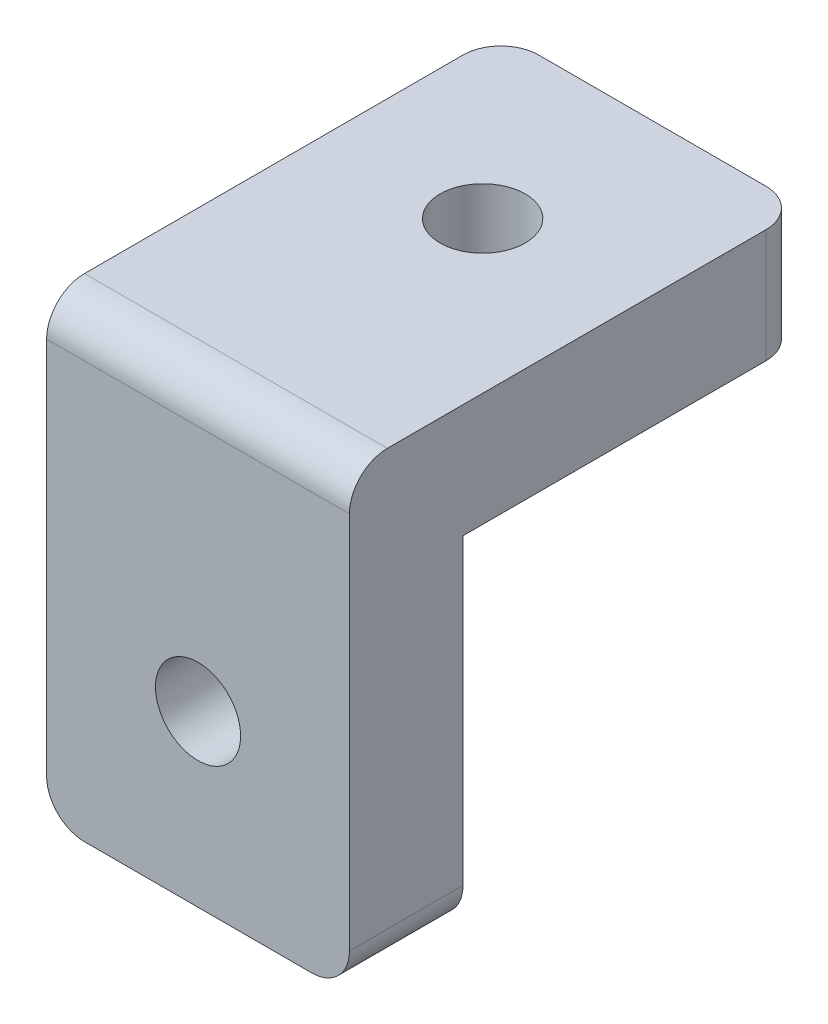
SolidWorks part; units mm, degrees
ref_plane "Front" through (0, 0, 0) normal (0, 0, 1) x (1, 0, 0)
ref_plane "Top" through (0, 0, 0) normal (0, 1, 0) x (1, 0, 0)
ref_plane "Right" through (0, 0, 0) normal (1, 0, 0) x (0, 0, -1)
sketch "Croquis1" plane through (0, 0, 0) normal (1, 0, 0) x (0, 0, -1)
  line L0 (-306.5372, 0) -> (15020.3218, 0) construction
  line L1 (0, -306.5372) -> (0, 15020.3218) construction
  line L2 (0, 0) -> (0, 12)
  line L3 (0, 12) -> (12, 12)
  line L4 (12, 12) -> (12, 9)
  line L5 (12, 9) -> (3, 9)
  line L6 (3, 9) -> (3, 0)
  line L7 (3, 0) -> (0, 0)
  dimension "D1" = 12
  dimension "D2" = 12
  dimension "D3" = 3
  dimension "D4" = 3
extrude "Saliente-Extruir1" add sketch "Croquis1" along normal blind 8
fillet "Redondeo1" radius 1 4 edges at (8, 0, -1.5) (0, 0, -1.5) (0, 10.5, -12) (8, 10.5, -12)
sketch "Croquis2" plane through (0, 9, 0) normal (0, -1, 0) x (1, 0, 0)
  line L0 (0.2929, -11.7071) -> (8, -3) construction
  line L1 (7.7071, -11.7071) -> (0, -3) construction
  arc A0 (0, -11) -> (1, -12) centre (1, -11) ccw construction
  arc A1 (7, -12) -> (8, -11) centre (7, -11) ccw construction
  circle A2 centre (4, -7.519) radius 1.125
  dimension "D1" = 2.25
extrude "Cortar-Extruir1" cut sketch "Croquis2" against normal through all
sketch "Croquis3" plane through (0, 0, -3) normal (0, 0, -1) x (-1, 0, 0)
  line L0 (-7.7071, 0.2929) -> (0, 9) construction
  line L1 (-0.2929, 0.2929) -> (-8, 9) construction
  arc A0 (-8, 1) -> (-7, 0) centre (-7, 1) ccw construction
  arc A1 (-1, 0) -> (0, 1) centre (-1, 1) ccw construction
  circle A2 centre (-4, 4.481) radius 1.125
  dimension "D1" = 2.25
extrude "Cortar-Extruir2" cut sketch "Croquis3" against normal through all
fillet "Redondeo2" radius 1 1 edges at (4, 12, 0)
